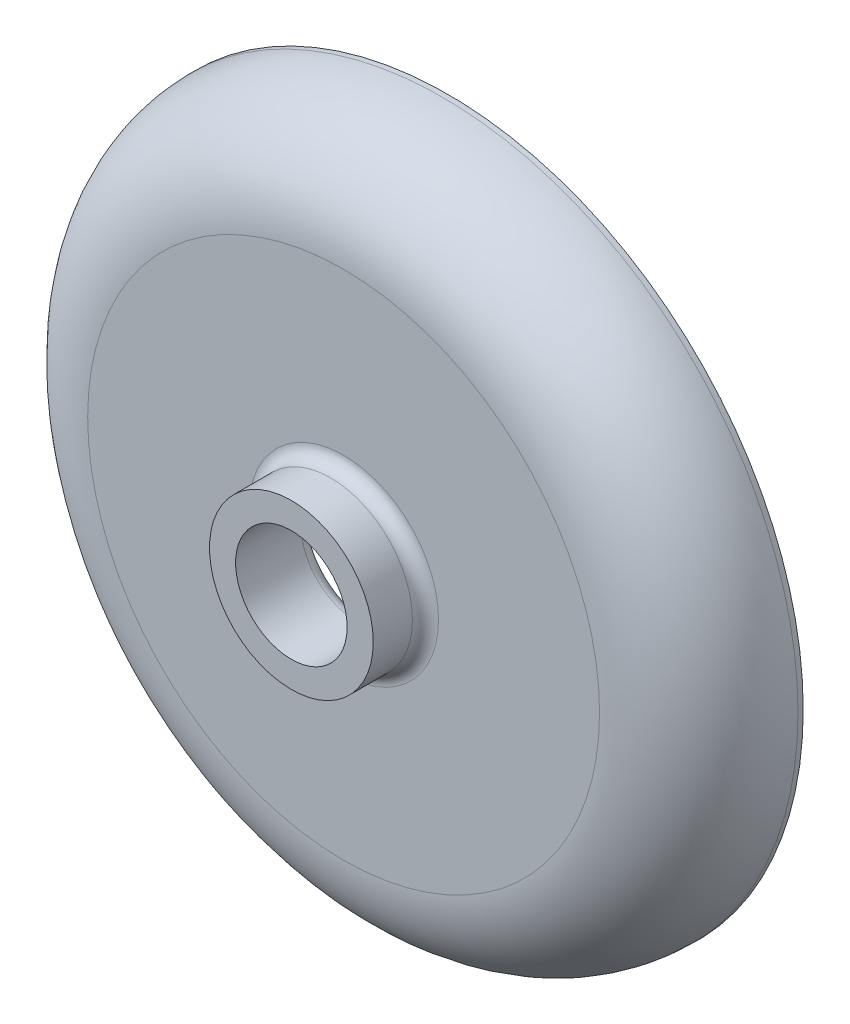
SolidWorks part; units mm, degrees
ref_plane "Plane1" through (0, 0, 0) normal (0, 0, 1) x (1, 0, 0)
ref_plane "Plane2" through (0, 0, 0) normal (0, 1, 0) x (1, 0, 0)
ref_plane "Plane3" through (0, 0, 0) normal (1, 0, 0) x (0, 0, -1)
sketch "Sketch1" plane through (0, 0, 0) normal (0, 0, 1) x (1, 0, 0)
  circle A0 centre (0, 0) radius 13.6
  dimension "D1" = 27.2
extrude "drive shaft plate shape" add sketch "Sketch1" along normal blind 4
fillet "plate main fillet" radius 3.8 1 edges at (13.6, 0, 4)
sketch "Sketch2" plane through (0, 0, 4) normal (0, 0, 1) x (1, 0, 0)
  circle A0 centre (0, 0) radius 3.135
  dimension "D1" = 6.27
extrude "plate boss" add sketch "Sketch2" along normal blind 2
shell "plate shell" thickness 1
sketch "Sketch3" plane through (0, 0, 6) normal (0, 0, 1) x (1, 0, 0)
  circle A0 centre (0, 0) radius 2.135
  dimension "D1" = 4.27
extrude "drive plate hole" cut sketch "Sketch3" against normal up to next
fillet "drive plate secondary fillet" radius 0.5 2 edges at (2.135, 0, 3) (3.135, 0, 4)
